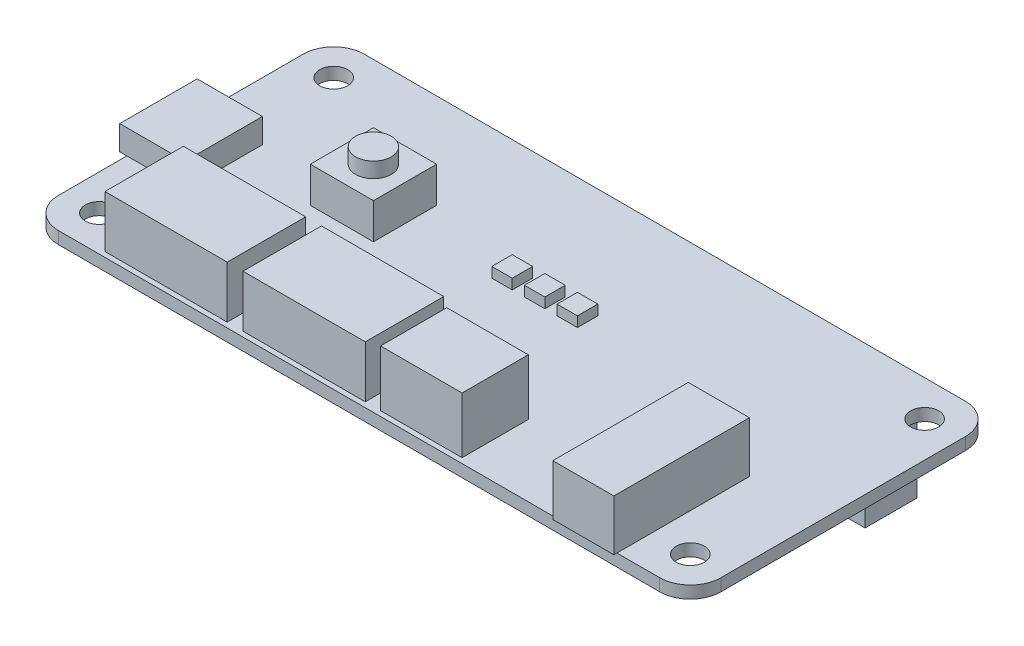
SolidWorks part; units mm, degrees
ref_plane "前视基准面" through (0, 0, 0) normal (0, 0, 1) x (1, 0, 0)
ref_plane "上视基准面" through (0, 0, 0) normal (0, 1, 0) x (1, 0, 0)
ref_plane "右视基准面" through (0, 0, 0) normal (1, 0, 0) x (0, 0, -1)
sketch "草图1" plane through (0, 0, 0) normal (0, 1, 0) x (1, 0, 0)
  line L1 (-29.5, 15) -> (29.5, 15)
  line L2 (-32.5, 12) -> (-32.5, -12)
  line L3 (-29.5, -15) -> (29.5, -15)
  line L4 (32.5, 12) -> (32.5, -12)
  line L5 (-32.5, 15) -> (32.5, -15) construction
  line L6 (-32.5, -15) -> (32.5, 15) construction
  arc A0 (29.5, 15) -> (32.5, 12) centre (29.5, 12) cw
  arc A1 (29.5, -15) -> (32.5, -12) centre (29.5, -12) ccw
  arc A2 (-32.5, -12) -> (-29.5, -15) centre (-29.5, -12) ccw
  arc A3 (-29.5, 15) -> (-32.5, 12) centre (-29.5, 12) ccw
  point P0 (0, 0)
  dimension "D3" = 3
  dimension "D1" = 65
  dimension "D2" = 30
extrude "凸台-拉伸1" add sketch "草图1" along normal blind 1.2
sketch "草图2" plane through (0, 1.2, 0) normal (0, 1, 0) x (1, 0, 0)
  line L0 (-29.5, -15) -> (29.5, -15) construction
  line L1 (32.5, -12) -> (32.5, 12) construction
  line L2 (29.5, 15) -> (-29.5, 15) construction
  circle A0 centre (29, -11.5) radius 1.375
  circle A1 centre (29, 11.5) radius 1.375
  circle A2 centre (-29, -11.5) radius 1.375
  circle A3 centre (-29, 11.5) radius 1.375
  point P15 (0, 0)
  point P16 (0, 0)
  point P17 (0, 0)
  point P18 (0, 0)
  dimension "D1" = 2.75
  dimension "D2" = 3.5
  dimension "D3" = 3.5
  dimension "D4" = 3.5
  dimension "D5" = 3.5
extrude "切除-拉伸1" cut sketch "草图2" against normal blind 1.2
sketch "草图3" plane through (0, 1.2, 0) normal (0, 1, 0) x (1, 0, 0)
  line L0 (-29.5, -15) -> (29.5, -15) construction
  line L1 (25.3, -15) -> (19.3, -15)
  line L2 (25.3, -15) -> (25.3, -2)
  line L3 (25.3, -2) -> (19.3, -2)
  line L4 (19.3, -15) -> (19.3, -2)
  line L5 (32.5, -12) -> (32.5, 12) construction
  dimension "D1" = 13
  dimension "D2" = 6
  dimension "D3" = 7.2
extrude "凸台-拉伸2" add sketch "草图3" along normal blind 5
sketch "草图4" plane through (0, 0, 15) normal (0, 0, 1) x (1, 0, 0)
  line L1 (19.3, 1.2) -> (25.3, 1.2)
  line L2 (19.3, 1.2) -> (19.3, 6.2)
  line L3 (19.3, 6.2) -> (25.3, 6.2)
  line L4 (25.3, 1.2) -> (25.3, 6.2)
extrude "凸台-拉伸3" add sketch "草图4" along normal blind 0.3
sketch "草图5" plane through (0, 1.2, 0) normal (0, 1, 0) x (1, 0, 0)
  line L0 (32.5, -12) -> (32.5, 12) construction
  line L1 (9.6, -8) -> (1.6, -8)
  line L2 (9.6, -8) -> (9.6, -15)
  line L3 (9.6, -15) -> (1.6, -15)
  line L4 (1.6, -8) -> (1.6, -15)
  line L5 (-29.5, -15) -> (19.3, -15) construction
  point P6 (0, 0)
  point P7 (0, 0)
  dimension "D1" = 22.9
  dimension "D2" = 7
  dimension "D3" = 8
extrude "凸台-拉伸4" add sketch "草图5" along normal blind 5.5
sketch "草图6" plane through (0, 1.2, 0) normal (0, 1, 0) x (1, 0, 0)
  line L0 (-29.5, -15) -> (1.6, -15) construction
  line L1 (0.1, -15) -> (-11.9, -15)
  line L2 (0.1, -15) -> (0.1, -6.8)
  line L3 (0.1, -6.8) -> (-11.9, -6.8)
  line L4 (-11.9, -15) -> (-11.9, -6.8)
  dimension "D1" = 8.2
  dimension "D2" = 12
  dimension "D3" = 1.5
extrude "凸台-拉伸5" add sketch "草图6" along normal blind 5.1
sketch "草图7" plane through (0, 1.2, 0) normal (0, 1, 0) x (1, 0, 0)
  line L0 (-29.5, -15) -> (-11.9, -15) construction
  line L1 (-13.45, -15) -> (-25.45, -15)
  line L2 (-13.45, -15) -> (-13.45, -6.8)
  line L3 (-13.45, -6.8) -> (-25.45, -6.8)
  line L4 (-25.45, -15) -> (-25.45, -6.8)
  dimension "D1" = 12
  dimension "D2" = 8.2
  dimension "D3" = 1.55
extrude "凸台-拉伸6" add sketch "草图7" along normal blind 5.1
sketch "草图8" plane through (0, 1.2, 0) normal (0, 1, 0) x (1, 0, 0)
  line L0 (-32.5, 12) -> (-32.5, -12) construction
  line L1 (-32.5, -5.3) -> (-26.8, -5.3)
  line L2 (-32.5, -5.3) -> (-32.5, 2.3)
  line L3 (-32.5, 2.3) -> (-26.8, 2.3)
  line L4 (-26.8, -5.3) -> (-26.8, 2.3)
  line L5 (-29.5, -15) -> (-25.45, -15) construction
  dimension "D1" = 9.7
  dimension "D2" = 7.6
  dimension "D3" = 5.7
extrude "凸台-拉伸7" add sketch "草图8" along normal blind 2.4
sketch "草图9" plane through (-32.5, 0, 0) normal (-1, 0, 0) x (0, 0, 1)
  line L1 (-2.3, 3.6) -> (5.3, 3.6)
  line L2 (-2.3, 3.6) -> (-2.3, 1.2)
  line L3 (-2.3, 1.2) -> (5.3, 1.2)
  line L4 (5.3, 3.6) -> (5.3, 1.2)
extrude "凸台-拉伸8" add sketch "草图9" along normal blind 0.7
sketch "草图10" plane through (0, 0, 15) normal (0, 0, 1) x (1, 0, 0)
  line L1 (-25.45, 6.3) -> (-13.45, 6.3)
  line L2 (-25.45, 6.3) -> (-25.45, 1.2)
  line L3 (-25.45, 1.2) -> (-13.45, 1.2)
  line L4 (-13.45, 6.3) -> (-13.45, 1.2)
  line L5 (-11.9, 6.3) -> (0.1, 6.3)
  line L6 (-11.9, 6.3) -> (-11.9, 1.2)
  line L7 (-11.9, 1.2) -> (0.1, 1.2)
  line L8 (0.1, 6.3) -> (0.1, 1.2)
  line L9 (1.6, 6.7) -> (9.6, 6.7)
  line L10 (1.6, 6.7) -> (1.6, 1.2)
  line L11 (1.6, 1.2) -> (9.6, 1.2)
  line L12 (9.6, 6.7) -> (9.6, 1.2)
extrude "切除-拉伸2" cut sketch "草图10" against normal blind 0.5
sketch "草图11" plane through (0, 0, 0) normal (0, -1, 0) x (1, 0, 0)
  line L0 (29.5, -15) -> (-29.5, -15) construction
  line L1 (25.65, -14.1) -> (-25.75, -14.1)
  line L2 (25.65, -14.1) -> (25.65, -9)
  line L3 (25.65, -9) -> (-25.75, -9)
  line L4 (-25.75, -14.1) -> (-25.75, -9)
  line L5 (32.5, 12) -> (32.5, -12) construction
  point P8 (32.5, -9.8368)
  point P13 (41.548, -11.0954)
  dimension "D1" = 51.4
  dimension "D2" = 5.1
  dimension "D3" = 0.9
  dimension "D4" = 6.85
extrude "凸台-拉伸9" add sketch "草图11" along normal blind 8.5
sketch "草图12" plane through (0, 1.2, 0) normal (0, 1, 0) x (1, 0, 0)
  line L0 (-32.5, 12) -> (-32.5, 2.3) construction
  line L1 (-13.1, -0.5) -> (-19.3, -0.5)
  line L2 (-13.1, -0.5) -> (-13.1, 5.7)
  line L3 (-13.1, 5.7) -> (-19.3, 5.7)
  line L4 (-19.3, -0.5) -> (-19.3, 5.7)
  line L5 (29.5, 15) -> (-29.5, 15) construction
  dimension "D1" = 6.2
  dimension "D2" = 6.2
  dimension "D3" = 13.2
  dimension "D4" = 9.3
extrude "凸台-拉伸10" add sketch "草图12" along normal blind 3.5
sketch "草图13" plane through (0, 4.7, 0) normal (0, 1, 0) x (1, 0, 0)
  circle A0 centre (-16.2, 2.6) radius 1.75
  dimension "D1" = 3.5
extrude "凸台-拉伸11" add sketch "草图13" along normal blind 1.5
sketch "草图14" plane through (0, 1.2, 0) normal (0, 1, 0) x (1, 0, 0)
  line L0 (29.5, 15) -> (-29.5, 15) construction
  line L1 (4.2, 2.22) -> (2.2, 2.22)
  line L2 (4.2, 2.22) -> (4.2, 4.22)
  line L3 (4.2, 4.22) -> (2.2, 4.22)
  line L4 (2.2, 2.22) -> (2.2, 4.22)
  line L13 (1, 2.22) -> (-1, 2.22)
  line L14 (1, 2.22) -> (1, 4.22)
  line L15 (1, 4.22) -> (-1, 4.22)
  line L16 (-1, 2.22) -> (-1, 4.22)
  line L17 (-2.2, 2.22) -> (-4.2, 2.22)
  line L18 (-2.2, 2.22) -> (-2.2, 4.22)
  line L19 (-2.2, 4.22) -> (-4.2, 4.22)
  line L20 (-4.2, 2.22) -> (-4.2, 4.22)
  line L21 (32.5, -12) -> (32.5, 12) construction
  point P12 (0, 0)
  dimension "D1" = 2
  dimension "D2" = 2
  dimension "D3" = 1.2
  dimension "D4" = 1.2
  dimension "D5" = 10.78
  dimension "D6" = 28.3
extrude "凸台-拉伸12" add sketch "草图14" along normal blind 1
